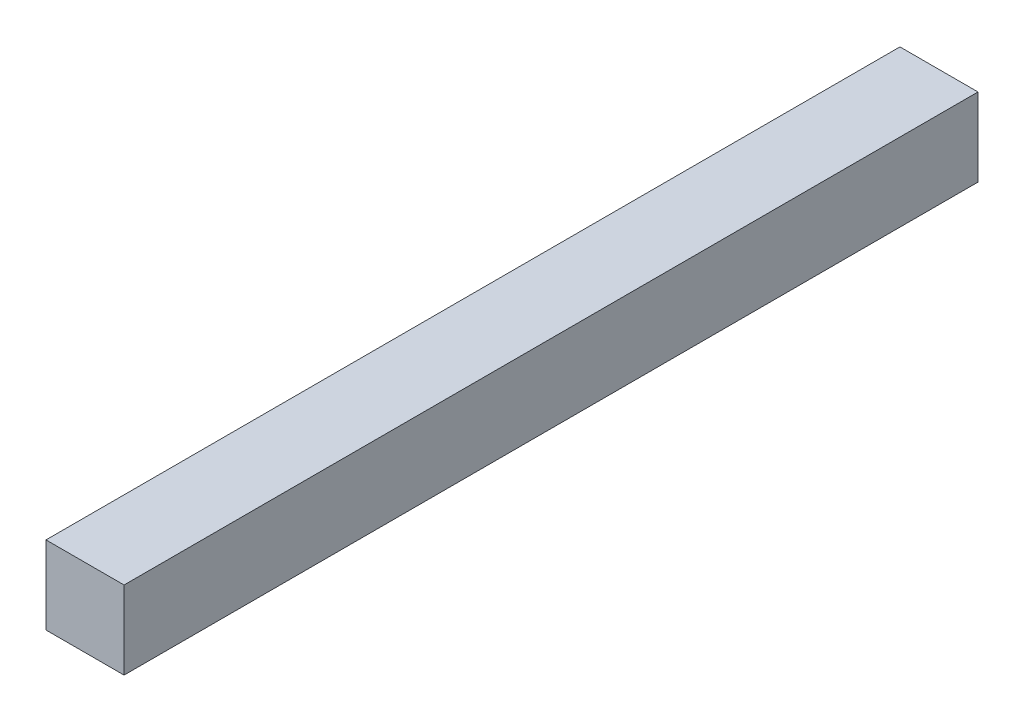
SolidWorks part; units mm, degrees
ref_plane "Front Plane" through (0, 0, 0) normal (0, 0, 1) x (1, 0, 0)
ref_plane "Top Plane" through (0, 0, 0) normal (0, 1, 0) x (1, 0, 0)
ref_plane "Right Plane" through (0, 0, 0) normal (1, 0, 0) x (0, 0, -1)
sketch "Sketch1" plane through (0, 0, 0) normal (0, 0, 1) x (1, 0, 0)
  line L1 (-1.6, -1.6) -> (1.6, -1.6)
  line L2 (-1.6, -1.6) -> (-1.6, 1.6)
  line L3 (-1.6, 1.6) -> (1.6, 1.6)
  line L4 (1.6, -1.6) -> (1.6, 1.6)
  line L5 (-1.6, -1.6) -> (1.6, 1.6) construction
  line L6 (-1.6, 1.6) -> (1.6, -1.6) construction
  point P0 (0, 0)
  dimension "D1" = 3.2
extrude "Boss-Extrude1" add sketch "Sketch1" along normal blind 35
